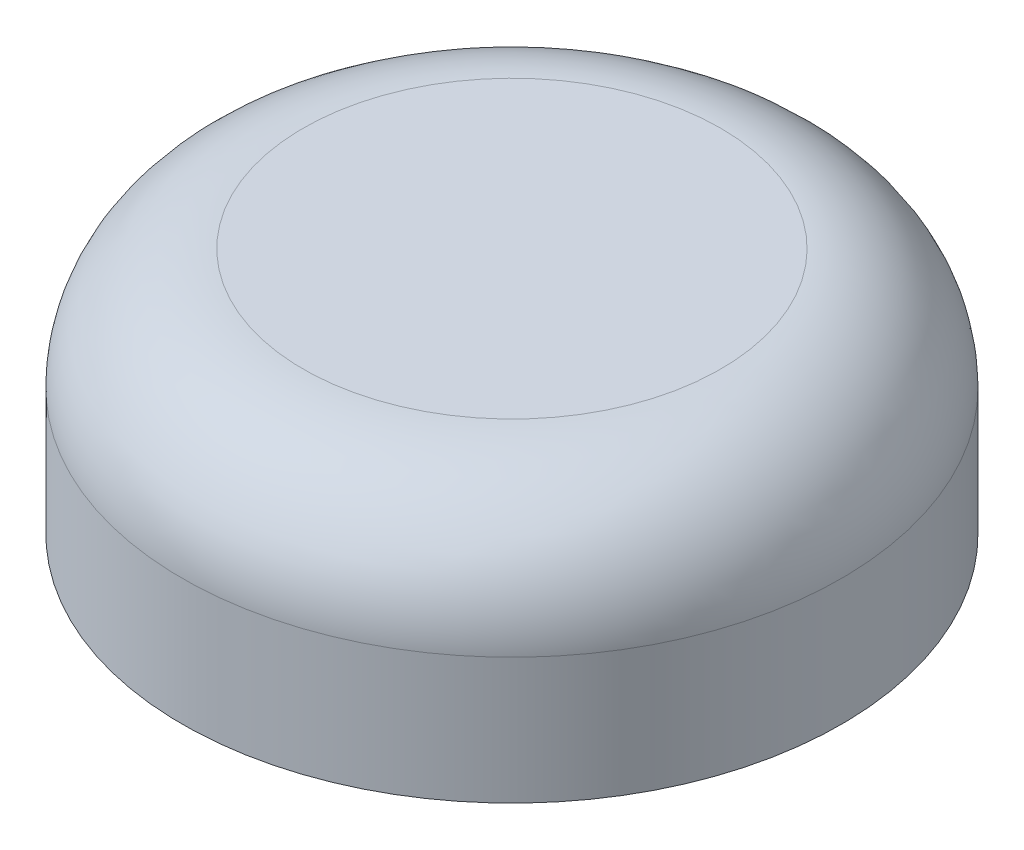
SolidWorks part; units mm, degrees
ref_plane "Front Plane" through (0, 0, 0) normal (0, 0, 1) x (1, 0, 0)
ref_plane "Top Plane" through (0, 0, 0) normal (0, 1, 0) x (1, 0, 0)
ref_plane "Right Plane" through (0, 0, 0) normal (1, 0, 0) x (0, 0, -1)
sketch "Sketch1" plane through (0, 0, 0) normal (0, 0, 1) x (1, 0, 0)
  line L0 (0, 0) -> (-24.13, 0)
  line L1 (-33.02, -8.89) -> (-33.02, -10.795)
  line L2 (-33.02, -10.795) -> (-35.56, -10.795)
  line L3 (-35.56, -10.795) -> (-35.56, -23.495)
  line L4 (-35.56, -23.495) -> (-38.1, -23.495)
  line L5 (-38.1, -23.495) -> (-38.1, -8.89)
  line L6 (0, 0) -> (0, 5.08)
  line L7 (0, 5.08) -> (-24.13, 5.08)
  line L8 (0, 0) -> (0, -23.495) construction
  line L9 (0, -23.495) -> (-35.56, -23.495) construction
  arc A0 (-24.13, 0) -> (-33.02, -8.89) centre (-24.13, -8.89) ccw
  arc A1 (-24.13, 5.08) -> (-38.1, -8.89) centre (-24.13, -8.89) ccw
  dimension "D7" = 8.89
  dimension "D1" = 2.54
  dimension "D2" = 5.08
  dimension "D3" = 5.08
  dimension "D4" = 76.2
  dimension "D5" = 12.7
  dimension "D6" = 28.575
revolve "Revolve1" add sketch "Sketch1" angle 360 about L6
